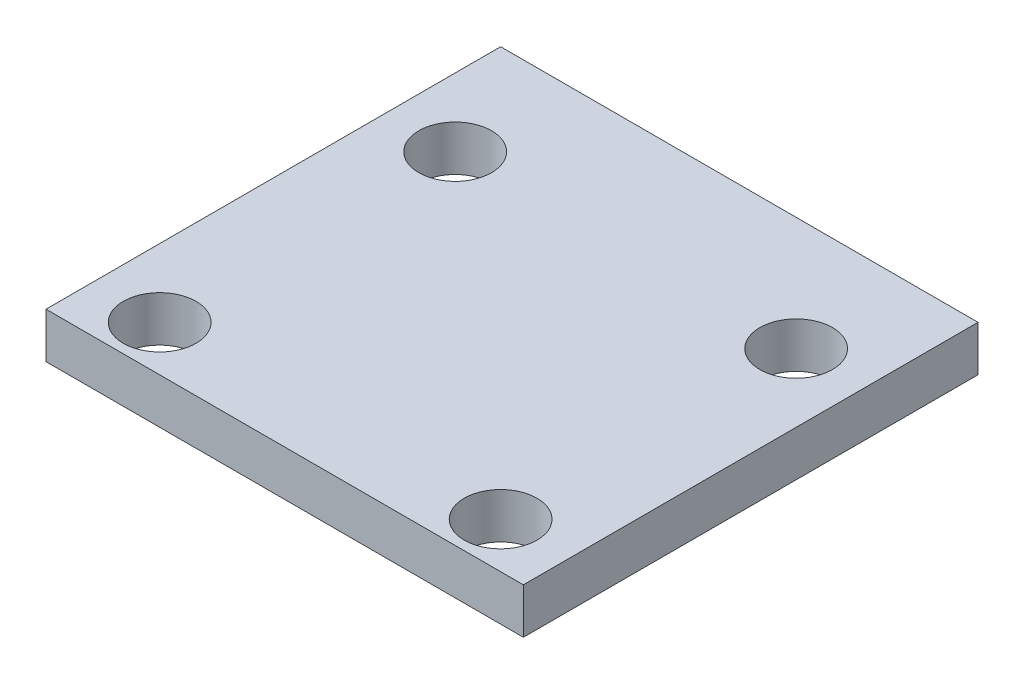
SolidWorks part; units mm, degrees
material "PET"
ref_plane "前视基准面" through (0, 0, 0) normal (0, 0, 1) x (1, 0, 0)
ref_plane "上视基准面" through (0, 0, 0) normal (0, 1, 0) x (1, 0, 0)
ref_plane "右视基准面" through (0, 0, 0) normal (1, 0, 0) x (0, 0, -1)
other "Configuration Table"
sketch "草图1" plane through (0, 0, 0) normal (0, 1, 0) x (1, 0, 0)
  line L1 (-10.5, 10) -> (10.5, 10)
  line L2 (-10.5, 10) -> (-10.5, -10)
  line L3 (-10.5, -10) -> (10.5, -10)
  line L4 (10.5, 10) -> (10.5, -10)
  line L5 (-10.5, 10) -> (10.5, -10) construction
  line L6 (-10.5, -10) -> (10.5, 10) construction
  point P0 (0, 0)
  dimension "D1" = 21
  dimension "D2" = 20
extrude "凸台-拉伸1" add sketch "草图1" along normal blind 2
sketch "草图2" plane through (0, 2, 0) normal (0, 1, 0) x (1, 0, 0)
  line L0 (-10.5, 5) -> (10.5, 5) construction
  line L1 (-10.5, 10) -> (-10.5, -10) construction
  line L2 (10.5, -10) -> (10.5, 10) construction
  line L3 (10.5, 10) -> (-10.5, 10) construction
  line L4 (0, 10) -> (0, -10) construction
  line L5 (-10.5, -10) -> (10.5, -10) construction
  line L6 (-7.5, 10) -> (-7.5, -10) construction
  line L7 (7.5, 10) -> (7.5, -10) construction
  circle A0 centre (-7.5, 5) radius 1.6
  circle A1 centre (-7.5, -8) radius 1.6
  circle A2 centre (7.5, -8) radius 1.6
  circle A3 centre (7.5, 5) radius 1.6
  dimension "D2" = 3.2
  dimension "D3" = 3.2
  dimension "D4" = 13
  dimension "D5" = 7.5
  dimension "D1" = 5
extrude "切除-拉伸1" cut sketch "草图2" against normal blind 2
